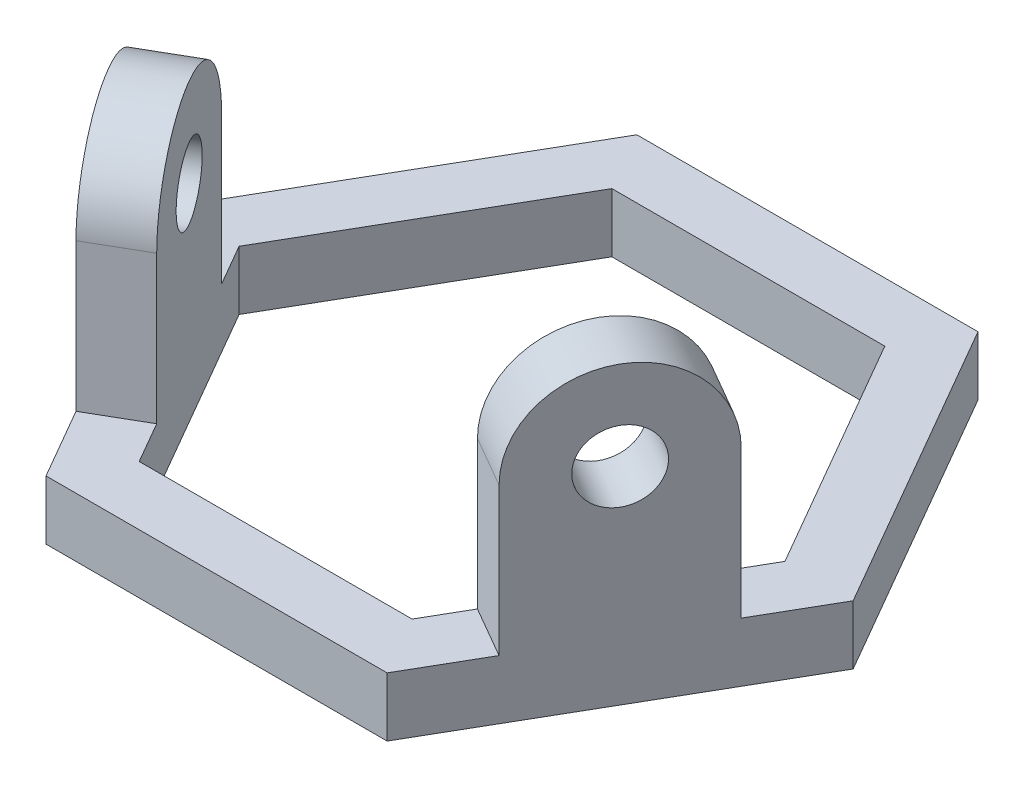
SolidWorks part; units mm, degrees
ref_plane "Front Plane" through (0, 0, 0) normal (0, 0, 1) x (1, 0, 0)
ref_plane "Top Plane" through (0, 0, 0) normal (0, 1, 0) x (1, 0, 0)
ref_plane "Right Plane" through (0, 0, 0) normal (1, 0, 0) x (0, 0, -1)
sketch "Sketch1" plane through (0, 0, 0) normal (0, 1, 0) x (1, 0, 0)
  line L0 (23.094, 40) -> (-23.094, 40)
  line L1 (57.735, 0) -> (28.8675, 50)
  line L2 (28.8675, 50) -> (-28.8675, 50)
  line L3 (-28.8675, 50) -> (-57.735, 0)
  line L4 (-57.735, 0) -> (-28.8675, -50)
  line L5 (-28.8675, -50) -> (28.8675, -50)
  line L6 (28.8675, -50) -> (57.735, 0)
  line L7 (-23.094, 40) -> (-46.188, 0)
  line L8 (-46.188, 0) -> (-23.094, -40)
  line L9 (-23.094, -40) -> (23.094, -40)
  line L10 (23.094, -40) -> (46.188, 0)
  line L11 (46.188, 0) -> (23.094, 40)
  circle A0 centre (0, 0) radius 50 construction
  dimension "D1" = 100
  dimension "D2" = 10
extrude "Boss-Extrude1" add sketch "Sketch1" along normal blind 10
sketch "Sketch2" plane through (43.3013, 0, 25) normal (0.866, 0, 0.5) x (0.5, 0, -0.866)
  line L0 (-15, 35) -> (-15, 10)
  line L1 (-28.8675, 10) -> (28.8675, 10) construction
  line L2 (15, 35) -> (15, 10)
  line L3 (15, 10) -> (-15, 10)
  line L4 (-28.8675, 0) -> (28.8675, 0) construction
  arc A0 (15, 35) -> (-15, 35) centre (0, 35) ccw
  circle A1 centre (0, 35) radius 6
  point P10 (0, 0)
  dimension "D1" = 35
  dimension "D2" = 15
  dimension "D3" = 12
extrude "Boss-Extrude2" add sketch "Sketch2" against normal blind 10
mirror "Mirror7" about plane through (0, 0, 0) normal (1, 0, 0) of "Boss-Extrude2"
